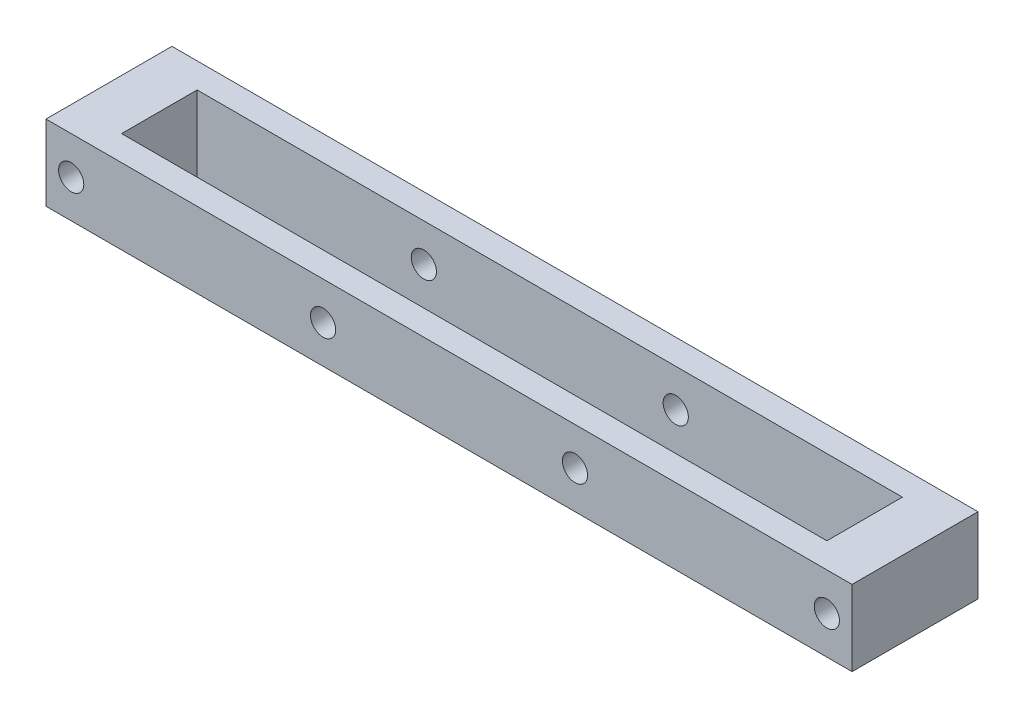
SolidWorks part; units mm, degrees
ref_plane "Front Plane" through (0, 0, 0) normal (0, 0, 1) x (1, 0, 0)
ref_plane "Top Plane" through (0, 0, 0) normal (0, 1, 0) x (1, 0, 0)
ref_plane "Right Plane" through (0, 0, 0) normal (1, 0, 0) x (0, 0, -1)
sketch "Sketch1" plane through (0, 0, 0) normal (0, 0, 1) x (1, 0, 0)
  line L1 (-160, 15) -> (160, 15)
  line L2 (-160, 15) -> (-160, -15)
  line L3 (-160, -15) -> (160, -15)
  line L4 (160, 15) -> (160, -15)
  line L5 (-160, 15) -> (160, -15) construction
  line L6 (-160, -15) -> (160, 15) construction
  point P0 (0, 0)
  dimension "D1" = 320
  dimension "D2" = 30
extrude "Boss-Extrude1" add sketch "Sketch1" along normal mid plane 50
sketch "Sketch2" plane through (0, 0, 0) normal (0, 1, 0) x (1, 0, 0)
  line L1 (-140, 15) -> (140, 15)
  line L2 (-140, 15) -> (-140, -15)
  line L3 (-140, -15) -> (140, -15)
  line L4 (140, 15) -> (140, -15)
  line L5 (-140, 15) -> (140, -15) construction
  line L6 (-140, -15) -> (140, 15) construction
  point P0 (0, 0)
  dimension "D1" = 280
  dimension "D2" = 30
extrude "Cut-Extrude1" cut sketch "Sketch2" against normal mid plane 50
sketch "Sketch3" plane through (0, 0, 0) normal (0, 0, 1) x (1, 0, 0)
  line L0 (-160, -15) -> (160, -15) construction
  line L1 (-160, 15) -> (-160, -15) construction
  line L2 (160, -15) -> (160, 15) construction
  circle A0 centre (-150, 0) radius 5
  circle A1 centre (150, 0) radius 5
  circle A2 centre (-50, 0) radius 5
  circle A3 centre (50, 0) radius 5
  dimension "D1" = 10
  dimension "D2" = 10
  dimension "D7" = 10
  dimension "D8" = 10
  dimension "D3" = 15
  dimension "D4" = 10
  dimension "D5" = 15
  dimension "D6" = 10
  dimension "D9" = 15
  dimension "D10" = 100
  dimension "D11" = 15
  dimension "D12" = 100
extrude "Cut-Extrude3" cut sketch "Sketch3" against normal through all both and the other way through all
